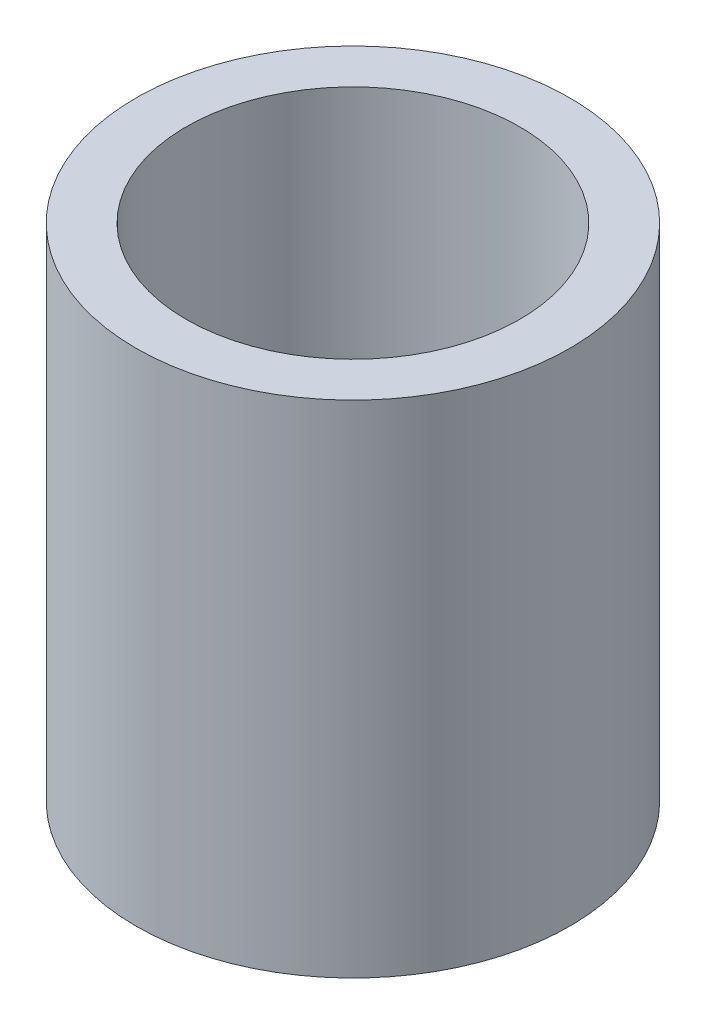
SolidWorks part; units mm, degrees
ref_plane "Front Plane" through (0, 0, 0) normal (0, 0, 1) x (1, 0, 0)
ref_plane "Top Plane" through (0, 0, 0) normal (0, 1, 0) x (1, 0, 0)
ref_plane "Right Plane" through (0, 0, 0) normal (1, 0, 0) x (0, 0, -1)
sketch "Sketch1" plane through (0, 0, 0) normal (0, 1, 0) x (1, 0, 0)
  circle A0 centre (0, 0) radius 2.6
  circle A1 centre (0, 0) radius 2
  dimension "D1" = 5.2
  dimension "D2" = 4
extrude "Boss-Extrude1" add sketch "Sketch1" along normal blind 6
